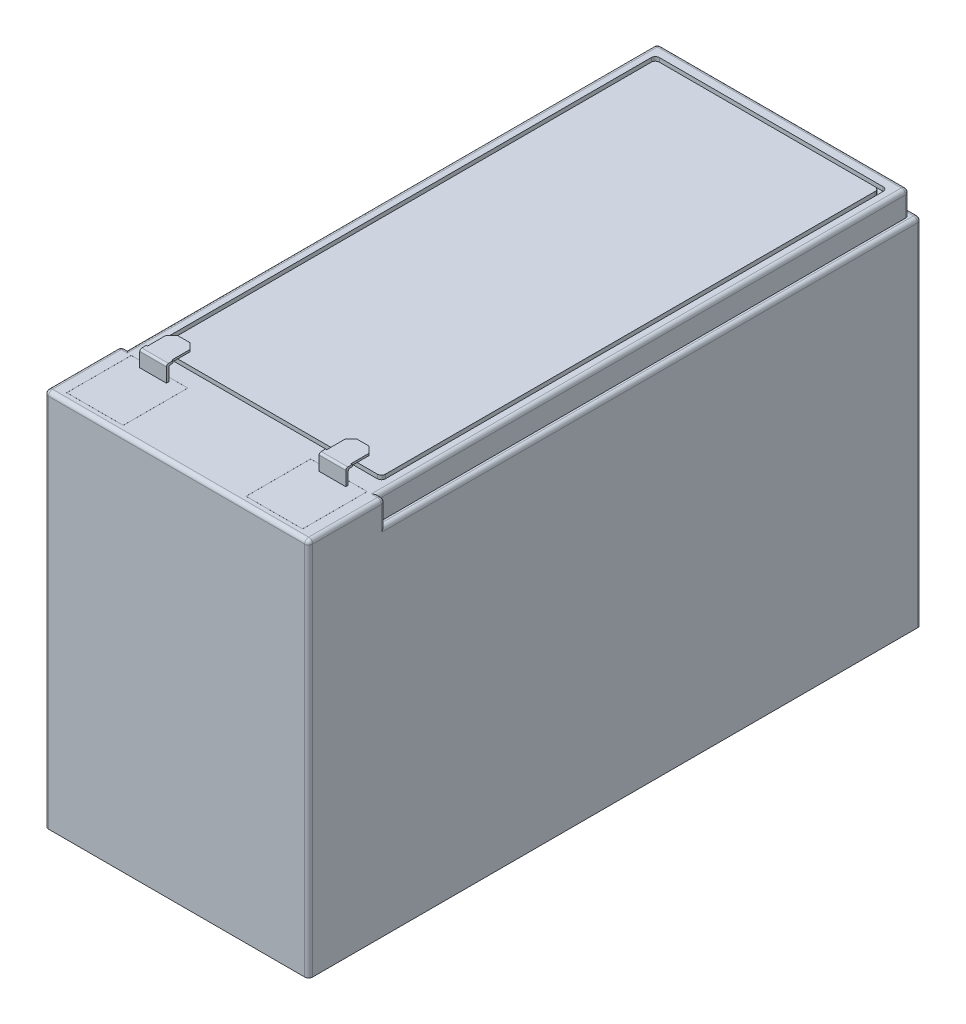
SolidWorks part; units mm, degrees
ref_plane "Alzado" through (0, 0, 0) normal (0, 0, 1) x (1, 0, 0)
ref_plane "Planta" through (0, 0, 0) normal (0, 1, 0) x (1, 0, 0)
ref_plane "Vista lateral" through (0, 0, 0) normal (1, 0, 0) x (0, 0, -1)
sketch "Croquis1" plane through (0, 0, 0) normal (0, 1, 0) x (1, 0, 0)
  line L1 (-32.7, 75.85) -> (32.7, 75.85)
  line L2 (-32.7, 75.85) -> (-32.7, -75.85)
  line L3 (-32.7, -75.85) -> (32.7, -75.85)
  line L4 (32.7, 75.85) -> (32.7, -75.85)
  line L5 (-32.7, 75.85) -> (32.7, -75.85) construction
  line L6 (-32.7, -75.85) -> (32.7, 75.85) construction
  point P0 (0, 0)
  dimension "D1" = 151.7
  dimension "D2" = 65.4
extrude "Saliente-Extruir1" add sketch "Croquis1" along normal blind 93.8
sketch "Croquis2" plane through (0, 93.8, 0) normal (0, 1, 0) x (1, 0, 0)
  line L0 (-32.7, -56.85) -> (-32.7, 75.85)
  line L1 (-32.7, 75.85) -> (-32.7, -75.85) construction
  line L2 (-32.7, 75.85) -> (32.7, 75.85)
  line L3 (32.7, 75.85) -> (32.7, -56.85)
  line L4 (32.7, -75.85) -> (32.7, 75.85) construction
  line L5 (32.7, -56.85) -> (31.2, -56.85)
  line L6 (31.2, -56.85) -> (31.2, 74.35)
  line L7 (31.2, 74.35) -> (-31.2, 74.35)
  line L8 (-31.2, 74.35) -> (-31.2, -56.85)
  line L9 (-31.2, -56.85) -> (-32.7, -56.85)
  line L10 (-32.7, -75.85) -> (32.7, -75.85) construction
  dimension "D1" = 19
  dimension "D2" = 1.5
  dimension "D3" = 1.5
  dimension "D4" = 19
  dimension "D5" = 1.5
extrude "Cortar-Extruir1" cut sketch "Croquis2" against normal blind 6
fillet "Redondeo1" radius 1 19 edges at (-31.95, 93.8, 56.85) (31.95, 93.8, 56.85) (-32.7, 93.8, 66.35) (32.7, 93.8, 66.35) (0, 93.8, 75.85) (31.2, 93.8, -8.75) (-31.2, 93.8, -8.75) (0, 93.8, -74.35) (-32.7, 87.8, -9.5) (0, 87.8, -75.85) (-32.7, 46.9, 75.85) (-32.7, 90.8, 56.85) (32.7, 90.8, 56.85) (-31.2, 90.8, -74.35) (31.2, 90.8, -74.35) (-32.7, 43.9, -75.85) (32.7, 43.9, -75.85) (32.7, 87.8, -9.5) (32.7, 46.9, 75.85)
sketch "Croquis3" plane through (0, 93.8, 0) normal (0, 1, 0) x (1, 0, 0)
  line L0 (-31.7, 74.85) -> (-31.7, -56.85) construction
  line L1 (-27.7, -53.85) -> (27.7, -53.85)
  line L2 (-28.7, -52.85) -> (-28.7, 70.35)
  line L3 (-27.7, 71.35) -> (27.7, 71.35)
  line L4 (28.7, -52.85) -> (28.7, 70.35)
  line L5 (-26.7, -52.85) -> (26.7, -52.85)
  line L6 (-27.7, -51.85) -> (-27.7, 69.35)
  line L7 (-26.7, 70.35) -> (26.7, 70.35)
  line L8 (27.7, -51.85) -> (27.7, 69.35)
  line L9 (31.7, -56.85) -> (31.7, 74.85) construction
  line L10 (-30.2, 74.35) -> (30.2, 74.35) construction
  arc A0 (-28.7, 70.35) -> (-27.7, 71.35) centre (-27.7, 70.35) cw
  arc A1 (-27.7, 69.35) -> (-26.7, 70.35) centre (-26.7, 69.35) cw
  arc A2 (27.7, 71.35) -> (28.7, 70.35) centre (27.7, 70.35) cw
  arc A3 (26.7, 70.35) -> (27.7, 69.35) centre (26.7, 69.35) cw
  arc A4 (-27.7, -53.85) -> (-28.7, -52.85) centre (-27.7, -52.85) cw
  arc A5 (-26.7, -52.85) -> (-27.7, -51.85) centre (-26.7, -51.85) cw
  arc A6 (27.7, -53.85) -> (28.7, -52.85) centre (27.7, -52.85) ccw
  arc A7 (26.7, -52.85) -> (27.7, -51.85) centre (26.7, -51.85) ccw
  dimension "D9" = 1
  dimension "D1" = 3
  dimension "D2" = 3
  dimension "D3" = 3
  dimension "D4" = 3
  dimension "D5" = 1
  dimension "D6" = 1
  dimension "D7" = 1
  dimension "D8" = 1
extrude "Cortar-Extruir2" cut sketch "Croquis3" against normal blind 1
sketch "Croquis4" plane through (0, 93.8, 0) normal (0, 1, 0) x (1, 0, 0)
  line L0 (-31.7, -74.85) -> (31.7, -74.85) construction
  line L1 (-29.2, -73.85) -> (-15.2, -73.85)
  line L2 (-29.2, -73.85) -> (-29.2, -57.85)
  line L3 (-29.2, -57.85) -> (-15.2, -57.85)
  line L4 (-15.2, -73.85) -> (-15.2, -57.85)
  line L5 (15.2, -73.85) -> (29.2, -73.85)
  line L6 (15.2, -73.85) -> (15.2, -57.85)
  line L7 (15.2, -57.85) -> (29.2, -57.85)
  line L8 (29.2, -73.85) -> (29.2, -57.85)
  line L9 (-31.7, -57.85) -> (-31.7, -74.85) construction
  line L10 (31.7, -74.85) -> (31.7, -57.85) construction
  line L12 (-29.19, -73.84) -> (-15.21, -73.84)
  line L13 (-29.19, -73.84) -> (-29.19, -57.86)
  line L14 (-29.19, -57.86) -> (-15.21, -57.86)
  line L15 (-15.21, -73.84) -> (-15.21, -57.86)
  line L16 (-29.19, -73.84) -> (-15.21, -57.86) construction
  line L17 (-29.19, -57.86) -> (-15.21, -73.84) construction
  line L18 (15.21, -73.84) -> (29.19, -73.84)
  line L19 (15.21, -73.84) -> (15.21, -57.86)
  line L20 (15.21, -57.86) -> (29.19, -57.86)
  line L21 (29.19, -73.84) -> (29.19, -57.86)
  line L22 (15.21, -73.84) -> (29.19, -57.86) construction
  line L23 (15.21, -57.86) -> (29.19, -73.84) construction
  point P14 (-22.2, -65.85)
  point P19 (22.2, -65.85)
  dimension "D1" = 16
  dimension "D2" = 14
  dimension "D3" = 14
  dimension "D4" = 1
  dimension "D5" = 2.5
  dimension "D6" = 2.5
  dimension "D7" = 0.01
  dimension "D8" = 0.01
  dimension "D9" = 0.01
  dimension "D10" = 0.01
  dimension "D11" = 0.01
  dimension "D12" = 0.01
  dimension "D13" = 0.01
  dimension "D14" = 0.01
extrude "Cortar-Extruir3" cut sketch "Croquis4" against normal blind 1
sketch "Croquis5" plane through (0, 93.8, 0) normal (0, 1, 0) x (1, 0, 0)
  line L0 (-15.21, -57.86) -> (-29.19, -57.86) construction
  line L1 (-25.5, -58.86) -> (-18.9, -58.86)
  line L2 (-25.5, -58.86) -> (-25.5, -59.46)
  line L3 (-25.5, -59.46) -> (-18.9, -59.46)
  line L4 (-18.9, -58.86) -> (-18.9, -59.46)
  line L5 (-25.5, -58.86) -> (-18.9, -59.46) construction
  line L6 (-25.5, -59.46) -> (-18.9, -58.86) construction
  line L7 (-15.2, -57.85) -> (-29.2, -57.85) construction
  line L8 (0, -86.3229) -> (0, -56.8401) construction
  line L9 (18.9, -58.86) -> (18.9, -59.46)
  line L10 (25.5, -58.86) -> (18.9, -58.86)
  line L11 (25.5, -58.86) -> (25.5, -59.46)
  line L12 (25.5, -59.46) -> (18.9, -59.46)
  point P0 (-22.2, -59.16)
  point P10 (-22.2, -57.85)
  dimension "D1" = 1
  dimension "D2" = 6.6
  dimension "D3" = 0.6
extrude "Saliente-Extruir2" add sketch "Croquis5" along normal blind 4
sketch "Croquis6" plane through (0, 0, 58.86) normal (0, 0, -1) x (-1, 0, 0)
  line L0 (25.5, 97.8) -> (25.5, 93.8) construction
  line L1 (18.9, 97.8) -> (25.5, 97.8)
  line L2 (18.9, 97.8) -> (18.9, 97.3)
  line L3 (18.9, 97.3) -> (25.5, 97.3)
  line L4 (25.5, 97.8) -> (25.5, 97.3)
  line L5 (0, 90.5945) -> (0, 99.4275) construction
  line L6 (-18.9, 97.8) -> (-18.9, 97.3)
  line L7 (-25.5, 97.8) -> (-25.5, 97.3)
  line L8 (-18.9, 97.3) -> (-25.5, 97.3)
  line L9 (-18.9, 97.8) -> (-25.5, 97.8)
  dimension "D1" = 0.5
extrude "Saliente-Extruir3" add sketch "Croquis6" along normal blind 1
sketch "Croquis7" plane through (0, 0, 57.86) normal (0, 0, -1) x (-1, 0, 0)
  line L0 (18.9, 97.3) -> (25.5, 97.3) construction
  line L1 (19.2, 97.8) -> (25.2, 97.8)
  line L2 (19.2, 97.8) -> (19.2, 97.3)
  line L3 (19.2, 97.3) -> (25.2, 97.3)
  line L4 (25.2, 97.8) -> (25.2, 97.3)
  line L5 (19.2, 97.8) -> (25.2, 97.3) construction
  line L6 (19.2, 97.3) -> (25.2, 97.8) construction
  line L7 (25.5, 97.8) -> (18.9, 97.8) construction
  line L9 (18.9, 97.8) -> (18.9, 97.3) construction
  line L10 (0, 101.0387) -> (0, 95.8279) construction
  line L11 (-19.2, 97.8) -> (-19.2, 97.3)
  line L12 (-25.2, 97.8) -> (-25.2, 97.3)
  line L13 (-19.2, 97.3) -> (-25.2, 97.3)
  line L14 (-19.2, 97.8) -> (-25.2, 97.8)
  point P0 (22.2, 97.55)
  point P10 (22.2, 97.8)
  point P14 (18.9, 97.55)
  dimension "D1" = 6
extrude "Saliente-Extruir4" add sketch "Croquis7" along normal blind 6
fillet "Redondeo2" radius 0.5 4 edges at (22.2, 97.3, 58.86) (-22.2, 97.3, 58.86) (-22.2, 97.8, 59.46) (22.2, 97.8, 59.46)
chamfer "Chaflán1" distance 1.5 angle 45 4 edges at (19.2, 97.55, 51.86) (25.2, 97.55, 51.86) (-19.2, 97.55, 51.86) (-25.2, 97.55, 51.86)
